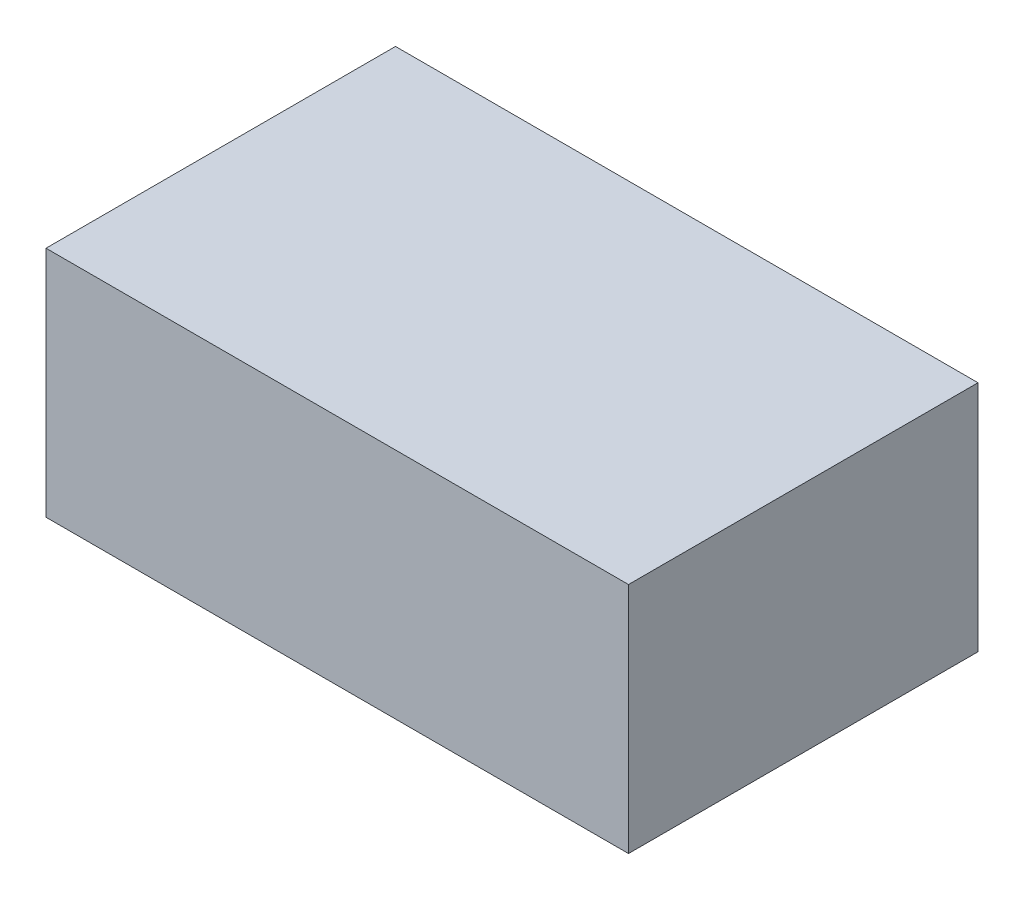
SolidWorks part; units mm, degrees
ref_plane "Alzado" through (0, 0, 0) normal (0, 0, 1) x (1, 0, 0)
ref_plane "Planta" through (0, 0, 0) normal (0, 1, 0) x (1, 0, 0)
ref_plane "Vista lateral" through (0, 0, 0) normal (1, 0, 0) x (0, 0, -1)
sketch "Croquis1" plane through (0, 0, 0) normal (0, 1, 0) x (1, 0, 0)
  line L1 (-25, 30) -> (25, 30)
  line L2 (-25, 30) -> (-25, 0)
  line L3 (-25, 0) -> (25, 0)
  line L4 (25, 30) -> (25, 0)
  dimension "D1" = 50
  dimension "D2" = 30
extrude "Saliente-Extruir1" add sketch "Croquis1" along normal blind 20
